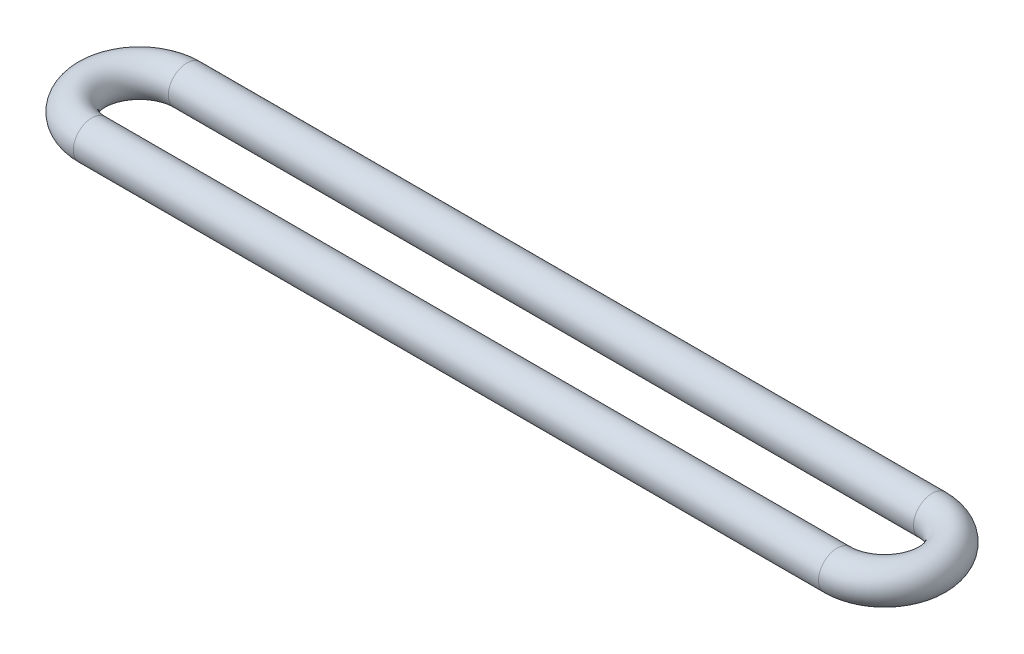
SolidWorks part; units mm, degrees
material "Natural Rubber"
ref_plane "Front" through (0, 0, 0) normal (0, 0, 1) x (1, 0, 0)
ref_plane "Top" through (0, 0, 0) normal (0, 1, 0) x (1, 0, 0)
ref_plane "Right" through (0, 0, 0) normal (1, 0, 0) x (0, 0, -1)
sketch "Sketch1" plane through (0, 0, 0) normal (0, 1, 0) x (1, 0, 0)
  line L0 (0, 0) -> (40, 0)
  line L1 (40, -5.1) -> (0, -5.1)
  arc A0 (40, 0) -> (40, -5.1) centre (40, -2.55) cw
  arc A1 (0, -5.1) -> (0, 0) centre (0, -2.55) cw
  dimension "D1" = 5.1
  dimension "D2" = 40
sketch "Sketch2" plane through (0, 0, 0) normal (1, 0, 0) x (0, 0, -1)
  circle A0 centre (0, 0) radius 1
  dimension "D1" = 2
sweep "Sweep1" add profiles "Sketch2" path "Sketch1"
